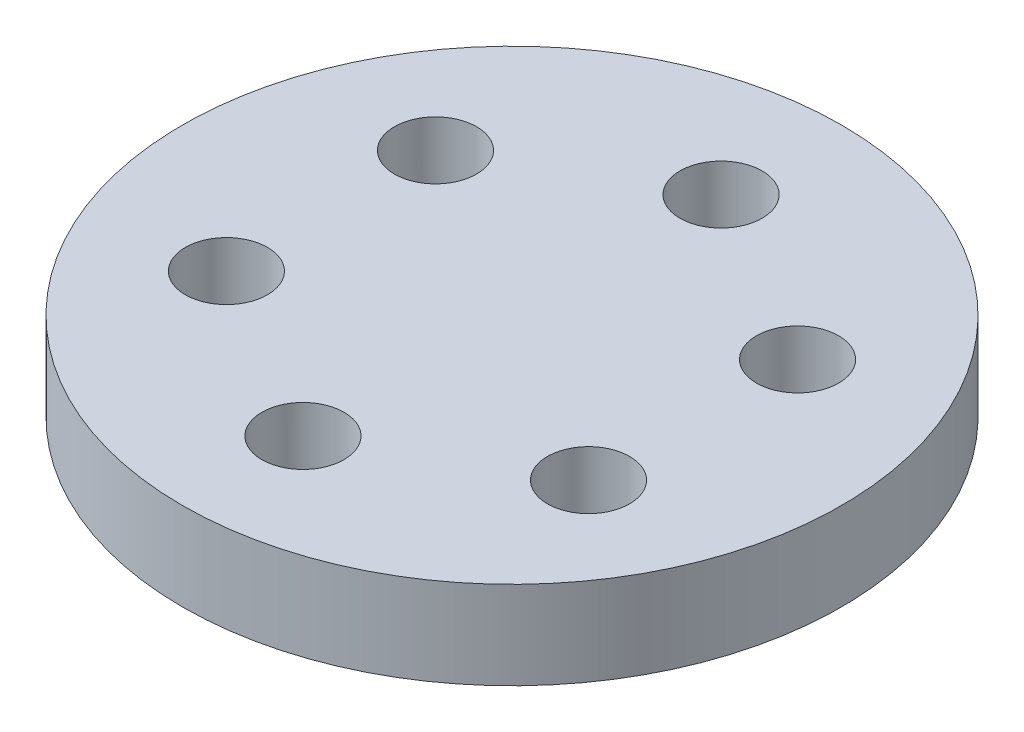
SolidWorks part; units mm, degrees
ref_plane "Front Plane" through (0, 0, 0) normal (0, 0, 1) x (1, 0, 0)
ref_plane "Top Plane" through (0, 0, 0) normal (0, 1, 0) x (1, 0, 0)
ref_plane "Right Plane" through (0, 0, 0) normal (1, 0, 0) x (0, 0, -1)
sketch "Sketch2" plane through (0, 0, 0) normal (0, 1, 0) x (1, 0, 0)
  circle A0 centre (0, 0) radius 38.1
  dimension "D1" = 76.2
extrude "Boss-Extrude1" add sketch "Sketch2" along normal blind 10.16
sketch "Sketch3" plane through (0, 10.16, 0) normal (0, 1, 0) x (1, 0, 0)
  circle A1 centre (0, 0) radius 24.1688 construction
  circle A2 centre (0, 24.1688) radius 4.7492
  dimension "D2" = 9.4985
  dimension "D1" = 24.1688
extrude "Cut-Extrude3" cut sketch "Sketch3" against normal blind 25.4
pattern_circular "CirPattern1" count 6 over 360 about axis through (0, 0, 0) along (0, 1, 0) of "Cut-Extrude3"
